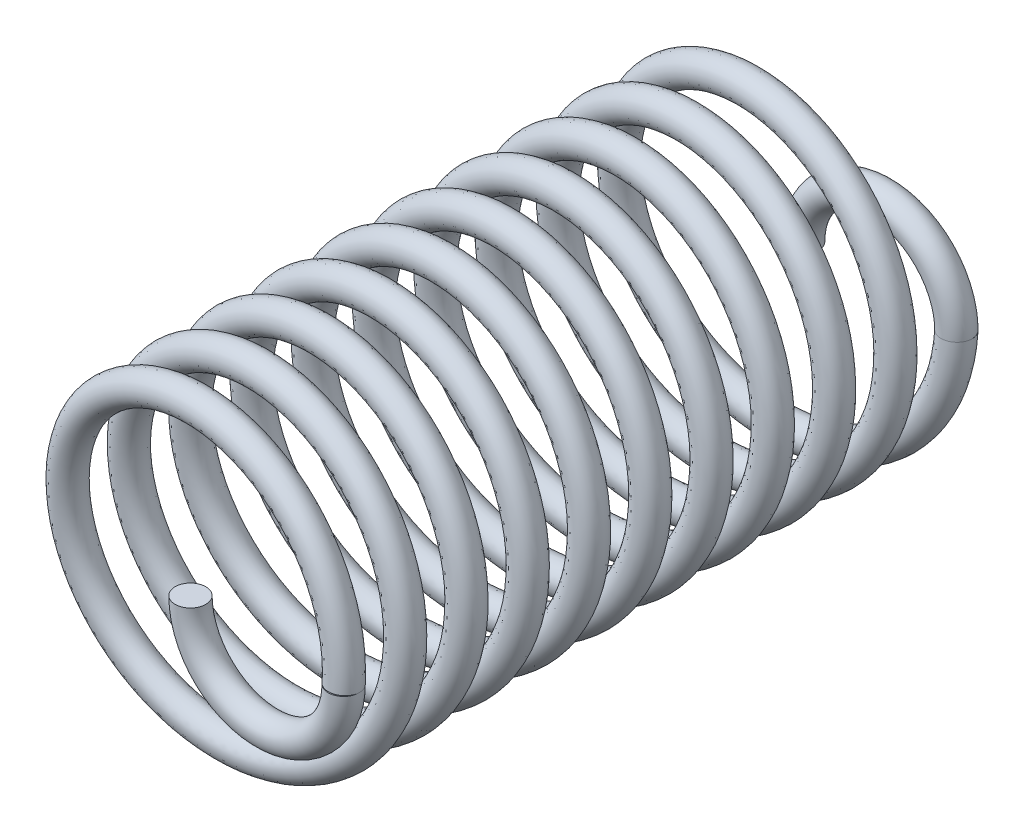
SolidWorks part; units mm, degrees
ref_plane "正面" through (0, 0, 0) normal (0, 0, 1) x (1, 0, 0)
ref_plane "平面" through (0, 0, 0) normal (0, 1, 0) x (1, 0, 0)
ref_plane "右側面" through (0, 0, 0) normal (1, 0, 0) x (0, 0, -1)
sketch "ｽｹｯﾁ1" plane through (0, 0, 0) normal (0, 0, 1) x (1, 0, 0)
  circle A0 centre (0, 0) radius 50
curve "ﾍﾘｶﾙ ｶｰﾌﾞ/ｽﾊﾟｲﾗﾙ ｶｰﾌﾞ1" pitch 20 height 200 turns 10
sketch "ｽｹｯﾁ2" plane through (0, 0, 0) normal (0, 1, 0) x (1, 0, 0)
  line L0 (0, 0) -> (0, -50000) construction
sketch "ｽｹｯﾁ3" plane through (0, 0, 0) normal (0, 0, 1) x (1, 0, 0)
  arc A0 (0, 0) -> (50, 0) centre (25, 0) cw
ref_plane "平面1" through (0, 0, 200) normal (0, 0, 1) x (1, 0, 0)
sketch "ｽｹｯﾁ4" plane through (0, 0, 200) normal (0, 0, 1) x (1, 0, 0)
  arc A0 (0, 0) -> (50, 0) centre (25, 0) ccw
sweep "ｽｲｰﾌﾟ1" add path "ｽｹｯﾁ4" circular profile diameter 10 parameters "D3"=10
sweep "ｽｲｰﾌﾟ2" add path "ﾍﾘｶﾙ ｶｰﾌﾞ/ｽﾊﾟｲﾗﾙ ｶｰﾌﾞ1" circular profile diameter 10 parameters "D3"=10
sweep "ｽｲｰﾌﾟ3" add path "ｽｹｯﾁ3" circular profile diameter 10 parameters "D3"=10
